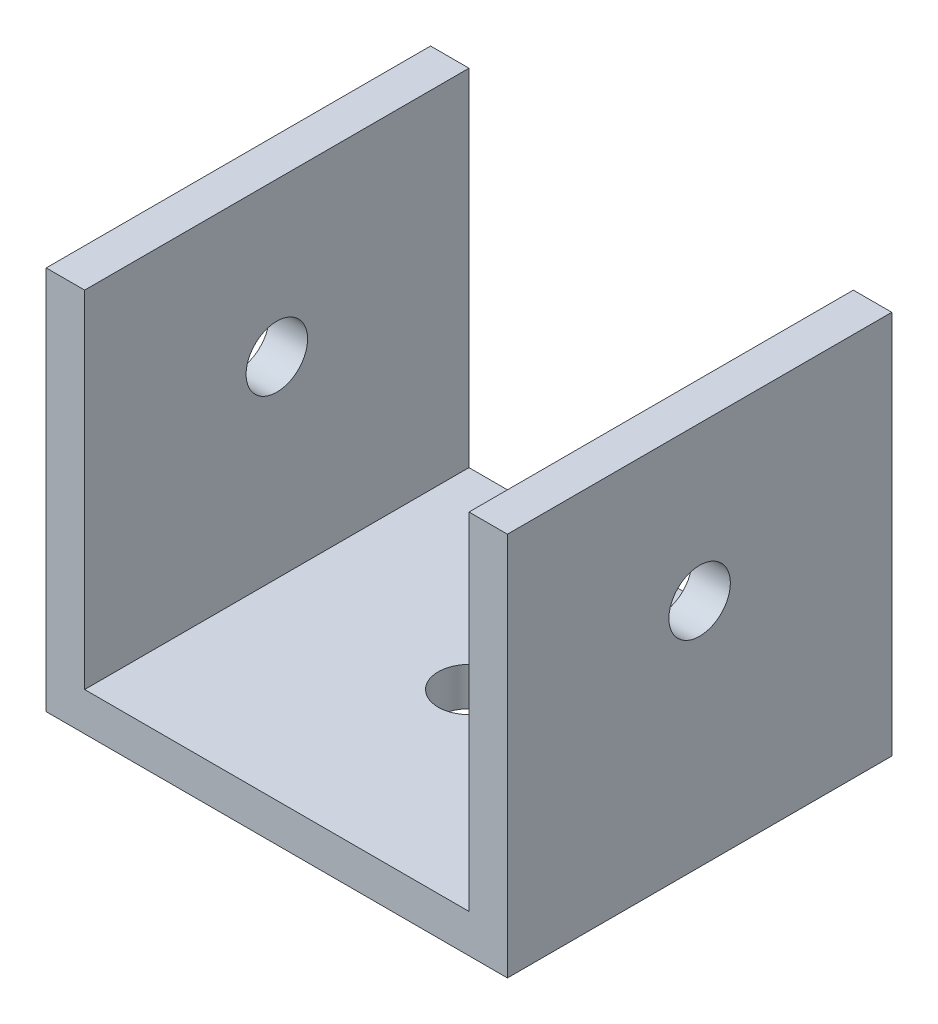
SolidWorks part; units mm, degrees
ref_plane "前视基准面" through (0, 0, 0) normal (0, 0, 1) x (1, 0, 0)
ref_plane "上视基准面" through (0, 0, 0) normal (0, 1, 0) x (1, 0, 0)
ref_plane "右视基准面" through (0, 0, 0) normal (1, 0, 0) x (0, 0, -1)
other "Configuration Table"
sketch "草图1" plane through (0, 0, 0) normal (0, 1, 0) x (1, 0, 0)
  line L1 (-25, 25) -> (25, 25)
  line L2 (-25, 25) -> (-25, -25)
  line L3 (-25, -25) -> (25, -25)
  line L4 (25, 25) -> (25, -25)
  line L5 (-25, 25) -> (25, -25) construction
  line L6 (-25, -25) -> (25, 25) construction
  point P0 (0, 0)
  dimension "D1" = 50
  dimension "D2" = 50
extrude "凸台-拉伸1" add sketch "草图1" along normal blind 5
sketch "草图2" plane through (25, 0, 0) normal (1, 0, 0) x (0, 0, -1)
  line L0 (25, 5) -> (25, 0) construction
  line L1 (-25, 0) -> (25, 0)
  line L2 (-25, 0) -> (-25, 50)
  line L3 (-25, 50) -> (25, 50)
  line L4 (25, 0) -> (25, 50)
  dimension "D1" = 50
extrude "凸台-拉伸2" add sketch "草图2" along normal blind 5
mirror "镜向1" about plane through (0, 0, 0) normal (1, 0, 0) of "凸台-拉伸2"
sketch "草图3" plane through (0, 5, 0) normal (0, 1, 0) x (1, 0, 0)
  circle A0 centre (0, 0) radius 4
  dimension "D1" = 8
extrude "切除-拉伸1" cut sketch "草图3" against normal blind 10
sketch "草图4" plane through (30, 0, 0) normal (1, 0, 0) x (0, 0, -1)
  line L0 (0, -8.7962) -> (0, 45.0524) construction
  line L1 (-25, 0) -> (25, 0) construction
  circle A0 centre (0, 30) radius 4
  dimension "D1" = 8
  dimension "D2" = 30
extrude "切除-拉伸2" cut sketch "草图4" against normal through all
